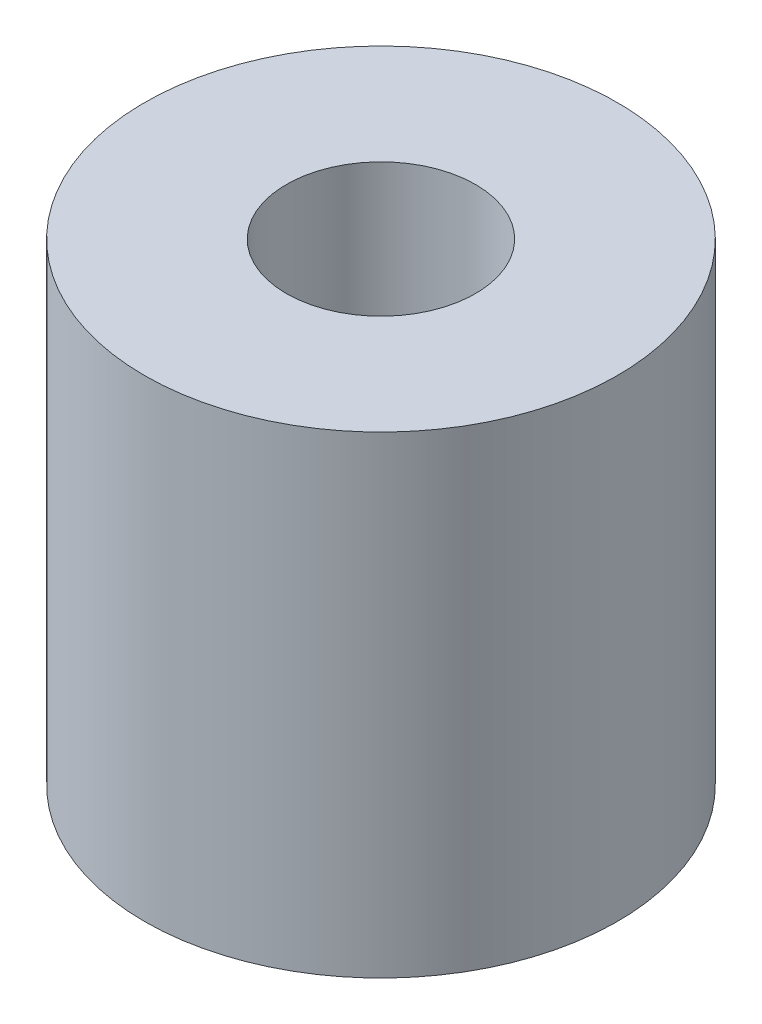
SolidWorks part; units mm, degrees
ref_plane "Front Plane" through (0, 0, 0) normal (0, 0, 1) x (1, 0, 0)
ref_plane "Top Plane" through (0, 0, 0) normal (0, 1, 0) x (1, 0, 0)
ref_plane "Right Plane" through (0, 0, 0) normal (1, 0, 0) x (0, 0, -1)
sketch "Sketch1" plane through (0, 0, 0) normal (0, 1, 0) x (1, 0, 0)
  circle A15 centre (0, 0) radius 2.5
  circle A16 centre (0, 0) radius 1
  dimension "D1" = 5
  dimension "D2" = 2
extrude "Boss-Extrude1" add sketch "Sketch1" along normal blind 5
equation "\"Arduino mounting hole diameter\"= 2mm"
equation "\"Arduino spacer diameter\"= 5mm"
equation "\"D1@Sketch1\"=\"Arduino spacer diameter\""
equation "\"Arduino spacer height\"= 5mm"
equation "\"D1@Boss-Extrude1\"=\"Arduino spacer height\""
